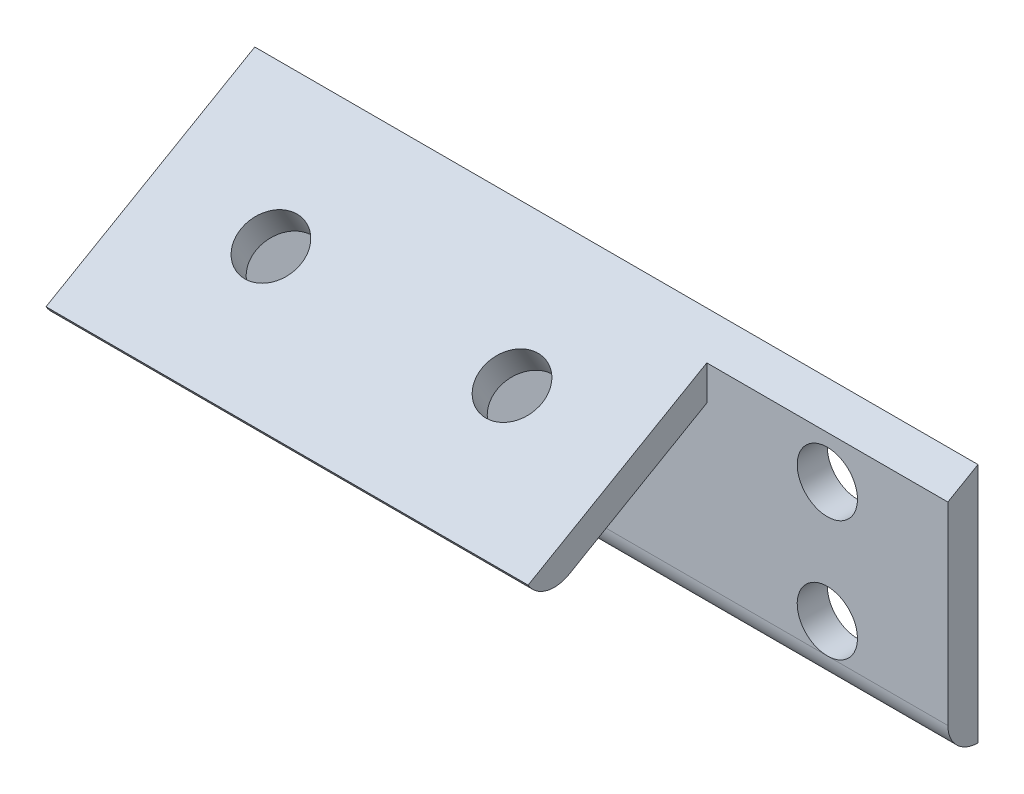
SolidWorks part; units mm, degrees
material "6061-T6 (SS)"
ref_plane "Front Plane" through (0, 0, 0) normal (0, 0, 1) x (1, 0, 0)
ref_plane "Top Plane" through (0, 0, 0) normal (0, 1, 0) x (1, 0, 0)
ref_plane "Right Plane" through (0, 0, 0) normal (1, 0, 0) x (0, 0, -1)
sketch "Sketch1" plane through (0, 0, 0) normal (1, 0, 0) x (0, 0, -1)
  line L0 (0, 0) -> (0, -25.4)
  line L1 (0, 0) -> (-21.997, -12.7)
  line L2 (-17.6599, -13.8621) -> (-3.175, -5.4993)
  line L3 (-3.175, -5.4993) -> (-3.175, -22.225)
  line L4 (-10.9985, -6.35) -> (-9.411, -9.0996) construction
  line L5 (0, -12.7) -> (-3.175, -12.7) construction
  arc A0 (-21.997, -12.7) -> (-17.6599, -13.8621) centre (-19.2474, -11.1125) ccw
  arc A1 (0, -25.4) -> (-3.175, -22.225) centre (0, -22.225) cw
  dimension "D1" = 25.4
  dimension "D2" = 60
  dimension "D3" = 3.175
extrude "Boss-Extrude1" add sketch "Sketch1" along normal blind 76.2
sketch "Sketch3" plane through (0, 0, 0) normal (0, 1, 0) x (1, 0, 0)
  line L0 (76.2, -3.175) -> (0, -3.175) construction
  line L1 (76.2, -3.175) -> (0, -3.175) construction
  line L2 (76.2, 0) -> (76.2, -21.997) construction
  line L3 (50.8, -3.175) -> (76.2, -3.175)
  line L4 (50.8, -3.175) -> (50.8, -28.575)
  line L5 (50.8, -28.575) -> (76.2, -28.575)
  line L6 (76.2, -3.175) -> (76.2, -28.575)
  dimension "D1" = 25.4
extrude "Cut-Extrude2" cut sketch "Sketch3" against normal up to next
hole_wizard "1/4 (0.25) Diameter Hole1" positions "Sketch5" profile "Sketch6" hole size "1/4" standard "ANSI Inch" end condition up to next
sketch "Sketch5" plane through (0, 0, 3.175) normal (0, 0, 1) x (1, 0, 0)
  line L0 (76.2, -1.8331) -> (76.2, -22.225) construction
  line L1 (76.2, 0) -> (0, 0) construction
  line L2 (76.2, -25.4) -> (0, -25.4) construction
  point P0 (63.5, -6.35)
  point P2 (63.5, -19.05)
  dimension "D1" = 12.7
  dimension "D2" = 6.35
  dimension "D3" = 6.35
sketch "Sketch6" plane through (63.5, -6.35, 3.175) normal (1, 0, 0) x (0, -1, 0)
  line L0 (0, 0) -> (0, 3.175)
  line L1 (0, 3.175) -> (3.175, 3.175)
  line L2 (3.175, 3.175) -> (3.175, 0)
  line L5 (3.175, 0) -> (0, 0)
  line L11 (0, -6.35) -> (0, 107.95) construction
  dimension "Thru Hole Dia." = 6.35
  dimension "Thru Hole Depth" = 3.175
hole_wizard "1/4 (0.25) Diameter Hole2" positions "Sketch10" profile "Sketch11" hole size "1/4" standard "ANSI Inch"
sketch "Sketch10" plane through (0, 0, 0) normal (0, 0.866, 0.5) x (1, 0, 0)
  line L0 (0, -12.7) -> (50.8, -12.7) construction
  line L1 (0, 0) -> (0, -25.4) construction
  line L2 (50.8, -3.6662) -> (50.8, -25.4) construction
  point P8 (12.7, -12.7)
  point P10 (38.1, -12.7)
  dimension "D1" = 12.7
  dimension "D2" = 12.7
sketch "Sketch11" plane through (12.7, -6.35, 10.9985) normal (1, 0, 0) x (0, -0.5, 0.866)
  line L0 (0, 0) -> (0, 3.175)
  line L1 (0, 3.175) -> (3.175, 3.175)
  line L2 (3.175, 3.175) -> (3.175, 0)
  line L5 (3.175, 0) -> (0, 0)
  line L11 (0, -6.35) -> (0, 107.95) construction
  dimension "Thru Hole Dia." = 6.35
  dimension "Thru Hole Depth" = 3.175
